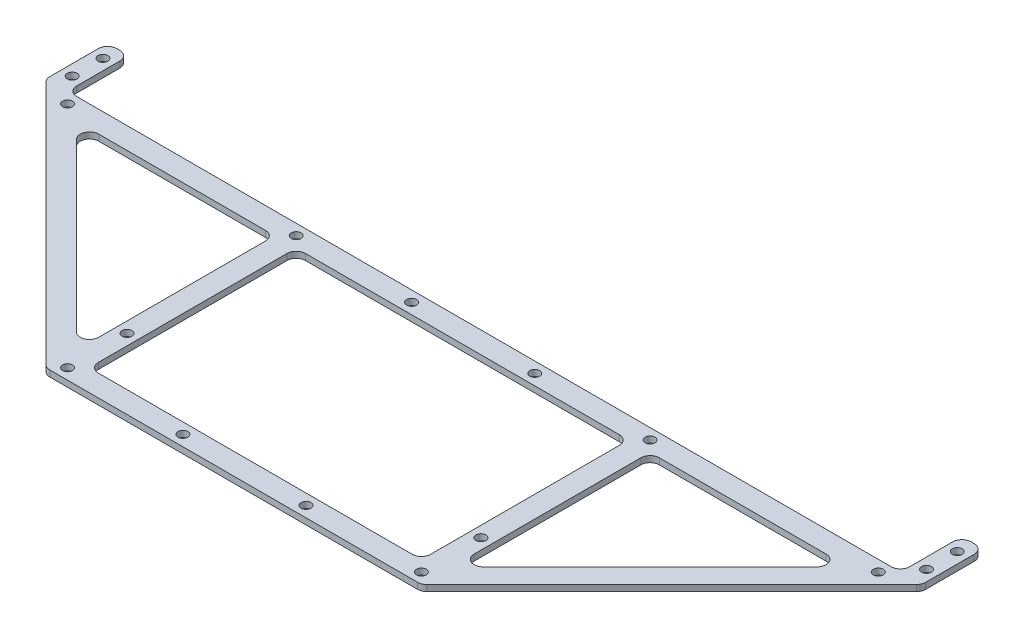
SolidWorks part; units mm, degrees
material "6061 合金"
ref_plane "正面" through (0, 0, 0) normal (0, 0, 1) x (1, 0, 0)
ref_plane "平面" through (0, 0, 0) normal (0, 1, 0) x (1, 0, 0)
ref_plane "右側面" through (0, 0, 0) normal (1, 0, 0) x (0, 0, -1)
sketch "ｽｹｯﾁ1" plane through (0, 0, 0) normal (0, 1, 0) x (1, 0, 0)
  line L0 (-61, 40.6586) -> (-135.3173, 40.6586)
  line L1 (54, -33.6586) -> (-54, -33.6586)
  line L2 (54, -33.6586) -> (54, 33.6586)
  line L3 (54, 33.6586) -> (-54, 33.6586)
  line L4 (-54, -33.6586) -> (-54, 33.6586)
  line L5 (54, -33.6586) -> (-54, 33.6586) construction
  line L6 (54, 33.6586) -> (-54, -33.6586) construction
  line L7 (61, -40.6586) -> (-61, -40.6586)
  line L9 (61, 40.6586) -> (-61, 40.6586)
  line L11 (61, -40.6586) -> (-61, 40.6586) construction
  line L12 (61, 40.6586) -> (-61, -40.6586) construction
  line L13 (-142.3173, 40.6586) -> (-61, -40.6586)
  line L14 (61, 40.6586) -> (135.3173, 40.6586)
  line L15 (142.3173, 40.6586) -> (61, -40.6586)
  line L16 (-125.4178, 33.6586) -> (-61, -30.7591)
  line L17 (-61, -30.7591) -> (-61, 33.6586)
  line L18 (-61, 33.6586) -> (-125.4178, 33.6586)
  line L19 (-61, 40.6586) -> (-61, -40.6586) construction
  line L20 (61, 40.6586) -> (61, -40.6586) construction
  line L21 (61, 33.6586) -> (61, -30.7591)
  line L22 (61, -30.7591) -> (125.4178, 33.6586)
  line L23 (125.4178, 33.6586) -> (61, 33.6586)
  line L24 (-57.5, 40.6586) -> (-57.5, -40.6586) construction
  line L25 (57.5, 40.6586) -> (57.5, -40.6586) construction
  line L26 (-61, -37.1586) -> (61, -37.1586) construction
  line L27 (-57.5, -37.1586) -> (-135.3173, 40.6586) construction
  line L28 (57.5, -37.1586) -> (135.3173, 40.6586) construction
  line L29 (57.5, 0) -> (-57.5, 0) construction
  line L30 (0, 40.6586) -> (0, -40.6586) construction
  line L31 (142.3173, 40.6586) -> (142.3173, 60.6586)
  line L32 (142.3173, 60.6586) -> (135.3173, 60.6586)
  line L33 (135.3173, 60.6586) -> (135.3173, 40.6586)
  line L34 (138.8173, 40.6586) -> (138.8173, 60.6586) construction
  line L35 (-135.3173, 40.6586) -> (-135.3173, 60.6586)
  line L36 (-135.3173, 60.6586) -> (-142.3173, 60.6586)
  line L37 (-142.3173, 60.6586) -> (-142.3173, 40.6586)
  line L38 (-138.8173, 60.6586) -> (-138.8173, 40.6586) construction
  circle A0 centre (-57.5, -37.1586) radius 1.6
  circle A1 centre (57.5, -37.1586) radius 1.6
  circle A2 centre (-131.7462, 37.0876) radius 1.6
  circle A3 centre (131.7462, 37.0876) radius 1.6
  circle A4 centre (20, -37.1586) radius 1.6
  circle A5 centre (-20, -37.1586) radius 1.6
  circle A6 centre (20, 37.1586) radius 1.6
  circle A7 centre (-20, 37.1586) radius 1.6
  circle A8 centre (57.5, 37.1586) radius 1.6
  circle A9 centre (57.5, -17.8414) radius 1.6
  circle A10 centre (-57.5, -17.8414) radius 1.6
  circle A11 centre (-57.5, 37.1586) radius 1.6
  circle A12 centre (138.8173, 55.6586) radius 1.6
  circle A13 centre (138.8173, 45.6586) radius 1.6
  circle A14 centre (-138.8173, 55.6586) radius 1.6
  circle A15 centre (-138.8173, 45.6586) radius 1.6
  point P0 (0, 0)
  point P6 (0, 0)
  point P41 (0, -37.1586)
  dimension "D14" = 105
  dimension "D15" = 105
  dimension "D16" = 3.2
  dimension "D17" = 20
  dimension "D18" = 40
  dimension "D19" = 3.5
  dimension "D20" = 55
  dimension "D23" = 15
  dimension "D24" = 20
  dimension "D25" = 15
  dimension "D26" = 5
  dimension "D1" = 45
  dimension "D2" = 45
  dimension "D3" = 7
  dimension "D4" = 7
  dimension "D5" = 115
  dimension "D6" = 108
  dimension "D7" = 122
  dimension "D8" = 7
  dimension "D9" = 7
  dimension "D10" = 7
  dimension "D11" = 3.5
  dimension "D12" = 3.5
  dimension "D13" = 3.5
  dimension "D21" = 7
  dimension "D22" = 5
  dimension "D27" = 20
extrude "ﾎﾞｽ - 押し出し1" add sketch "ｽｹｯﾁ1" along normal blind 2
fillet "ﾌｨﾚｯﾄ1" radius 3 20 edges at (-125.4178, 1, -33.6586) (-61, 1, 30.7591) (-61, 1, -33.6586) (-54, 1, 33.6586) (-54, 1, -33.6586) (54, 1, -33.6586) (54, 1, 33.6586) (61, 1, 30.7591) (61, 1, -33.6586) (125.4178, 1, -33.6586) (61, 1, 40.6586) (-61, 1, 40.6586) (-142.3173, 1, -40.6586) (-142.3173, 1, -60.6586) (-135.3173, 1, -60.6586) (-135.3173, 1, -40.6586) (135.3173, 1, -40.6586) (142.3173, 1, -60.6586) (135.3173, 1, -60.6586) (142.3173, 1, -40.6586)
